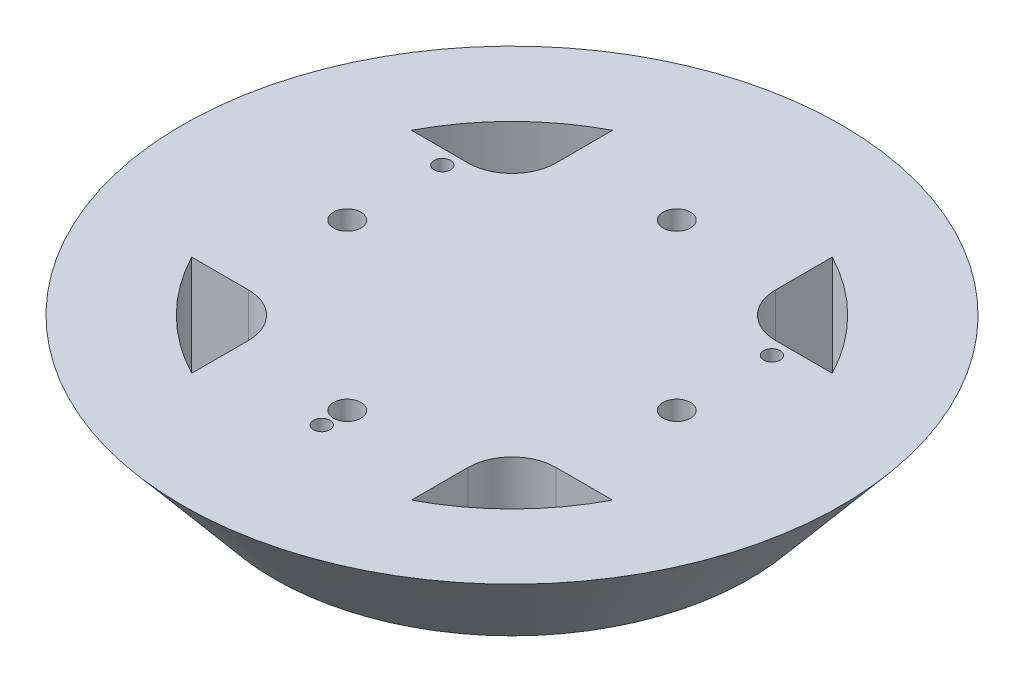
SolidWorks part; units mm, degrees
material "ABS"
ref_plane "Alzado" through (0, 0, 0) normal (0, 0, 1) x (1, 0, 0)
ref_plane "Planta" through (0, 0, 0) normal (0, 1, 0) x (1, 0, 0)
ref_plane "Vista lateral" through (0, 0, 0) normal (1, 0, 0) x (0, 0, -1)
sketch "Sketch1" plane through (0, 0, 0) normal (0, 1, 0) x (1, 0, 0)
  circle A0 centre (0, 0) radius 60
  dimension "D1" = 120
extrude "Boss-Extrude1" add sketch "Sketch1" against normal blind 20 draft 40
sketch "Sketch5" plane through (0, -20, 0) normal (0, -1, 0) x (1, 0, 0)
  line L0 (0, 0) -> (0, 43.218) construction
  line L6 (-20, 38.3118) -> (-20, 15)
  line L8 (20, 38.3118) -> (20, 15)
  line L9 (38.3118, 20) -> (15, 20)
  line L10 (0, 0) -> (43.218, 0) construction
  line L11 (38.3118, -20) -> (15, -20)
  line L12 (20, -38.3118) -> (20, -15)
  line L13 (0, 0) -> (0, -43.218) construction
  line L14 (-20, -38.3118) -> (-20, -15)
  line L19 (-38.3118, -20) -> (-15, -20)
  line L26 (0, 0) -> (-43.218, 0) construction
  line L27 (-38.3118, 20) -> (-15, 20)
  arc A2 (-20, 15) -> (-15, 20) centre (0, 0) ccw
  arc A4 (-15, -20) -> (-20, -15) centre (0, 0) ccw
  circle A5 centre (0, 0) radius 43.218 construction
  circle A7 centre (0, 0) radius 15
  circle A8 centre (0, 0) radius 43.218
  arc A9 (20, -15) -> (15, -20) centre (0, 0) ccw
  arc A10 (15, 20) -> (20, 15) centre (0, 0) ccw
  point P5 (0, -9.4703)
  point P25 (0, 0)
  point P30 (0, 0)
  dimension "D2" = 50
  dimension "D6" = 20
  dimension "D7" = 20
  dimension "47" = 30
  dimension "D8" = 20
  dimension "D1" = 40
  dimension "D4" = 20
  dimension "D5" = 40
  dimension "D9" = 20
  dimension "D3" = 4
extrude "Cut-Extrude1" cut sketch "Sketch5" against normal blind 25
hole_wizard "Ø3.0mm Dowel Hole1" positions "Sketch6" profile "Sketch7" hole size "Ø3.0" standard "ANSI Metric" end condition up to next
sketch "Sketch6" plane through (0, -20, 0) normal (0, -1, 0) x (-1, 0, 0)
  line L1 (0, 0) -> (0, -43.218) construction
  line L3 (0, 0) -> (-37.4279, 21.609) construction
  line L4 (0, 0) -> (37.4279, 21.609) construction
  circle A0 centre (0, 0) radius 43.218 construction
  point P0 (0, -34.64)
  point P11 (-29.9991, 17.32)
  point P12 (29.9991, 17.32)
  dimension "D1" = 34.64
  dimension "D3" = 34.64
  dimension "D4" = 34.64
  dimension "D2" = 3
  dimension "D5" = 3
sketch "Sketch7" plane through (0, -20, 34.64) normal (1, 0, 0) x (0, 0, -1)
  line L0 (0, 0) -> (0, 20)
  line L1 (0, 20) -> (1.5, 20)
  line L2 (1.5, 20) -> (1.5, 0)
  line L5 (1.5, 0) -> (0, 0)
  line L11 (0, -6.35) -> (0, 107.95) construction
  dimension "Thru Hole Dia." = 3
  dimension "Thru Hole Depth" = 20
fillet "Fillet1" radius 8 4 edges at (20, -10, 20) (20, -10, -20) (-20, -10, -20) (-20, -10, 20)
sketch "Sketch13" plane through (0, 0, 0) normal (0, 1, 0) x (1, 0, 0)
  line L0 (0, 60) -> (0, -60) construction
  line L1 (-60, 0) -> (60, 0) construction
  circle A0 centre (0, 0) radius 60 construction
  circle A1 centre (0, 30) radius 2.5
  circle A2 centre (0, -30) radius 2.5
  circle A3 centre (30, 0) radius 2.5
  circle A4 centre (0, -30) radius 2.5
  circle A5 centre (-30, 0) radius 2.5
  point P11 (0, 0)
  point P21 (0, 0)
  dimension "D1" = 5
  dimension "D2" = 5
  dimension "D7" = 30
  dimension "D3" = 60
  dimension "D4" = 30
  dimension "D6" = 60
  dimension "D5" = 4
extrude "Cut-Extrude5" cut sketch "Sketch13" against normal blind 10 contours A1 | A3 | A2 | A5
equation "\"diametro_exterior\"= \"D1@Sketch1\""
equation "\"D1@Sketch1\"=120"
equation "\"Diametro_Base\"= 30"
